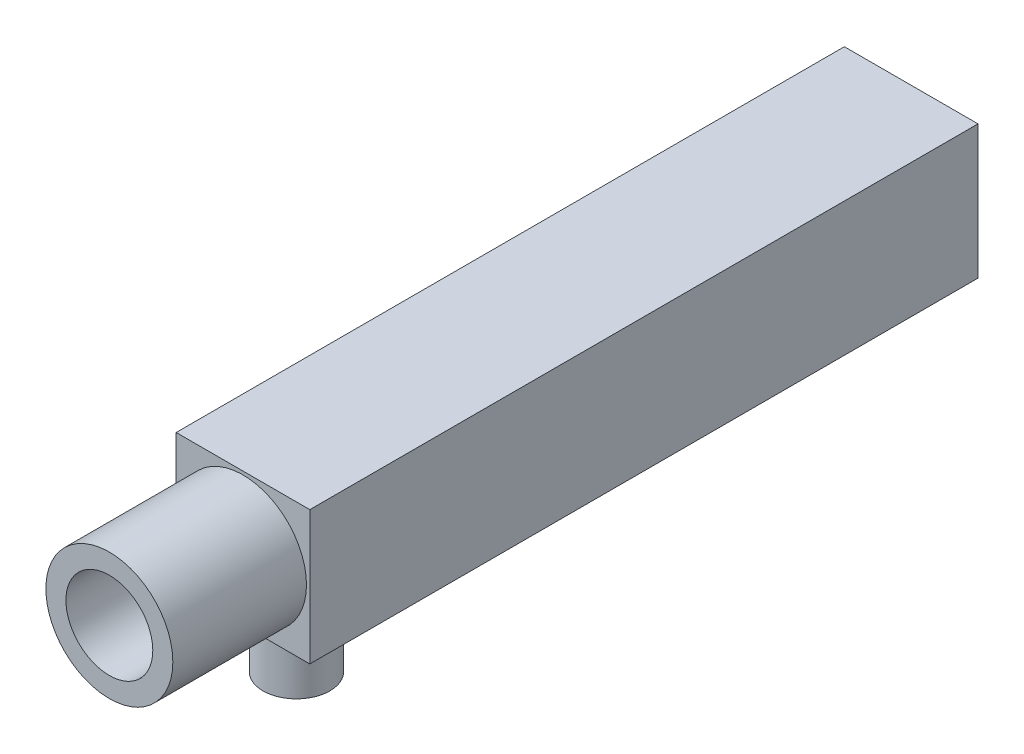
SolidWorks part; units mm, degrees
material "ABS"
ref_plane "Front Plane" through (0, 0, 0) normal (0, 0, 1) x (1, 0, 0)
ref_plane "Top Plane" through (0, 0, 0) normal (0, 1, 0) x (1, 0, 0)
ref_plane "Right Plane" through (0, 0, 0) normal (1, 0, 0) x (0, 0, -1)
sketch "Sketch1" plane through (0, 0, 0) normal (0, 0, 1) x (1, 0, 0)
  line L1 (0, 0) -> (-10, 0)
  line L2 (0, 0) -> (0, 10)
  line L3 (0, 10) -> (-10, 10)
  line L4 (-10, 0) -> (-10, 10)
  line L5 (-8.5, 8.5) -> (-1.5, 8.5)
  line L6 (-8.5, 8.5) -> (-8.5, 1.5)
  line L7 (-8.5, 1.5) -> (-1.5, 1.5)
  line L8 (-1.5, 8.5) -> (-1.5, 1.5)
  dimension "D1" = 10
  dimension "D2" = 10
  dimension "D3" = 1.5
  dimension "D4" = 1.5
  dimension "D5" = 1.5
  dimension "D6" = 1.5
extrude "Boss-Extrude1" add sketch "Sketch1" along normal blind 50
sketch "Sketch2" plane through (0, 0, 50) normal (0, 0, 1) x (1, 0, 0)
  line L1 (-8.5, 1.5) -> (-1.5, 1.5)
  line L2 (-8.5, 1.5) -> (-8.5, 8.5)
  line L3 (-8.5, 8.5) -> (-1.5, 8.5)
  line L4 (-1.5, 1.5) -> (-1.5, 8.5)
extrude "Boss-Extrude2" add sketch "Sketch2" against normal blind 5
sketch "Sketch3" plane through (0, 0, 50) normal (0, 0, 1) x (1, 0, 0)
  line L0 (-10, 10) -> (-10, 0) construction
  line L1 (-10, 0) -> (0, 0) construction
  circle A0 centre (-5, 5) radius 4
  dimension "D1" = 8
  dimension "D2" = 5
  dimension "D3" = 5
extrude "Cut-Extrude1" cut sketch "Sketch3" against normal blind 5
sketch "Sketch4" plane through (0, 0, 0) normal (0, -1, 0) x (1, 0, 0)
  line L0 (-10, 50) -> (0, 50) construction
  line L1 (-10, 50) -> (-10, 0) construction
  circle A0 centre (-5, 46) radius 2.5
  circle A1 centre (-5, 46) radius 0.5
  dimension "D1" = 5
  dimension "D2" = 1
  dimension "D3" = 4
  dimension "D4" = 5
extrude "Boss-Extrude3" add sketch "Sketch4" along normal blind 5
sketch "Sketch5" plane through (0, 0, 50) normal (0, 0, 1) x (1, 0, 0)
  circle A1 centre (-5, 5) radius 3.25
  circle A2 centre (-5, 5) radius 4.75
  dimension "D1" = 6.5
  dimension "D2" = 9.5
extrude "Boss-Extrude4" add sketch "Sketch5" along normal blind 10
